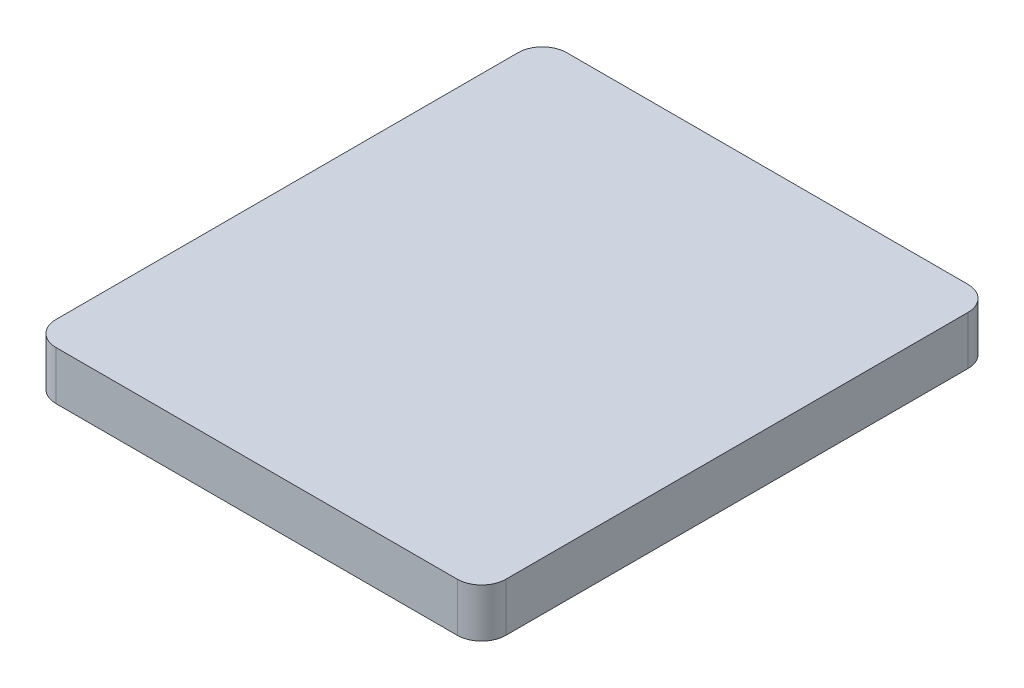
SolidWorks part; units mm, degrees
ref_plane "Front Plane" through (0, 0, 0) normal (0, 0, 1) x (1, 0, 0)
ref_plane "Top Plane" through (0, 0, 0) normal (0, 1, 0) x (1, 0, 0)
ref_plane "Right Plane" through (0, 0, 0) normal (1, 0, 0) x (0, 0, -1)
sketch "Sketch1" plane through (0, 0, 0) normal (0, 1, 0) x (1, 0, 0)
  line L1 (0, 0) -> (18.5, 0)
  line L2 (0, 0) -> (0, 21)
  line L3 (0, 21) -> (18.5, 21)
  line L4 (18.5, 0) -> (18.5, 21)
  dimension "D1" = 18.5
  dimension "D2" = 21
extrude "Boss-Extrude1" add sketch "Sketch1" along normal blind 2
fillet "Fillet1" radius 1 4 edges at (0, 1, -21) (18.5, 1, -21) (18.5, 1, 0) (0, 1, 0)
